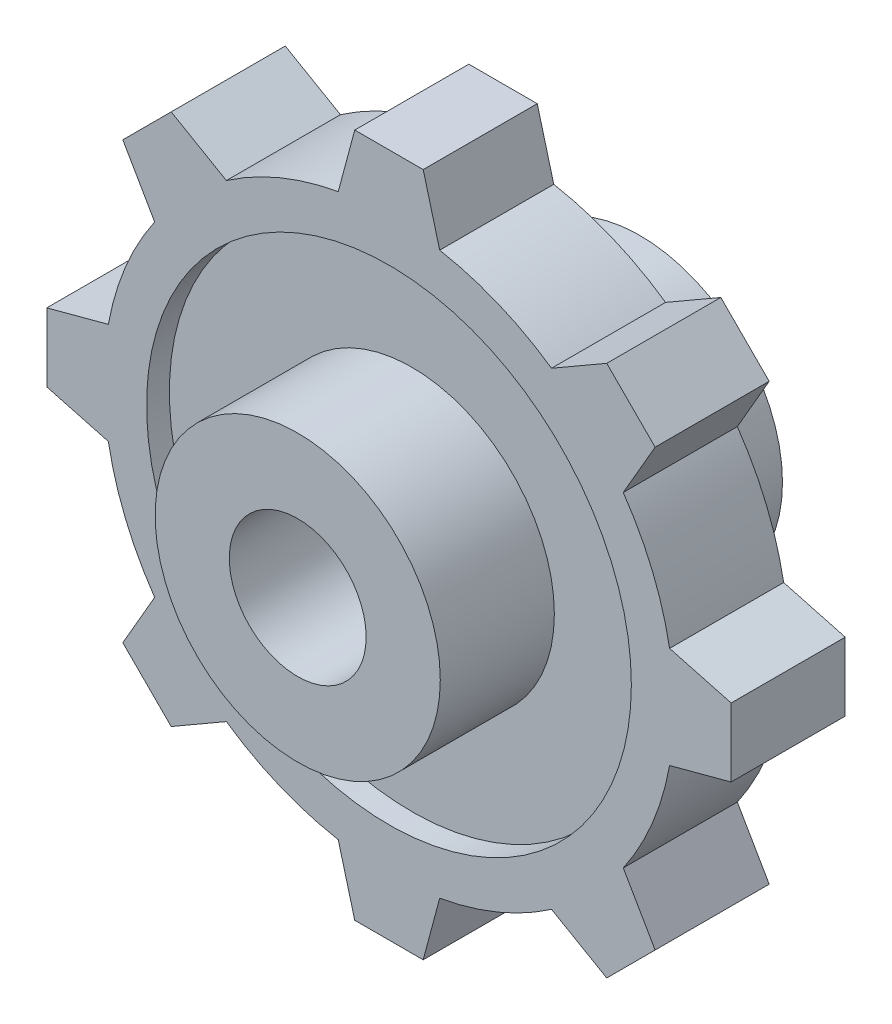
SolidWorks part; units mm, degrees
ref_plane "Front" through (0, 0, 0) normal (0, 0, 1) x (1, 0, 0)
ref_plane "Top" through (0, 0, 0) normal (0, 1, 0) x (1, 0, 0)
ref_plane "Right" through (0, 0, 0) normal (1, 0, 0) x (0, 0, -1)
sketch "Sketch1" plane through (0, 0, 0) normal (0, 0, 1) x (1, 0, 0)
  circle A0 centre (0, 0) radius 25
  dimension "D1" = 50
extrude "Extrude1" add sketch "Sketch1" along normal blind 10
sketch "Sketch2" plane through (0, 0, 10) normal (0, 0, 1) x (1, 0, 0)
  line L0 (0, 0) -> (0, 56.6434) construction
  line L1 (-3, 30) -> (3, 30)
  line L2 (3, 30) -> (5.6795, 20)
  line L3 (5.6795, 20) -> (-5.6795, 20)
  line L4 (-5.6795, 20) -> (-3, 30)
  point P5 (0, 20)
  point P8 (0, 30)
  dimension "D1" = 20
  dimension "D2" = 30
  dimension "D3" = 3
  dimension "D4" = 75
extrude "Extrude2" add sketch "Sketch2" against normal blind 10
pattern_circular "CirPattern1" count 8 over 360 about axis through (0, 0, 0) along (0, 0, 1) of "Extrude2"
sketch "Sketch3" plane through (0, 0, 10) normal (0, 0, 1) x (1, 0, 0)
  circle A0 centre (0, 0) radius 21.25
  dimension "D1" = 42.5
extrude "Cut-Extrude1" cut sketch "Sketch3" against normal blind 2
sketch "Sketch4" plane through (0, 0, 8) normal (0, 0, 1) x (1, 0, 0)
  circle A0 centre (0, 0) radius 6
  circle A1 centre (0, 0) radius 12.5
  dimension "D1" = 12
  dimension "D2" = 25
extrude "Extrude3" add sketch "Sketch4" along normal blind 10 and the other way blind 20
